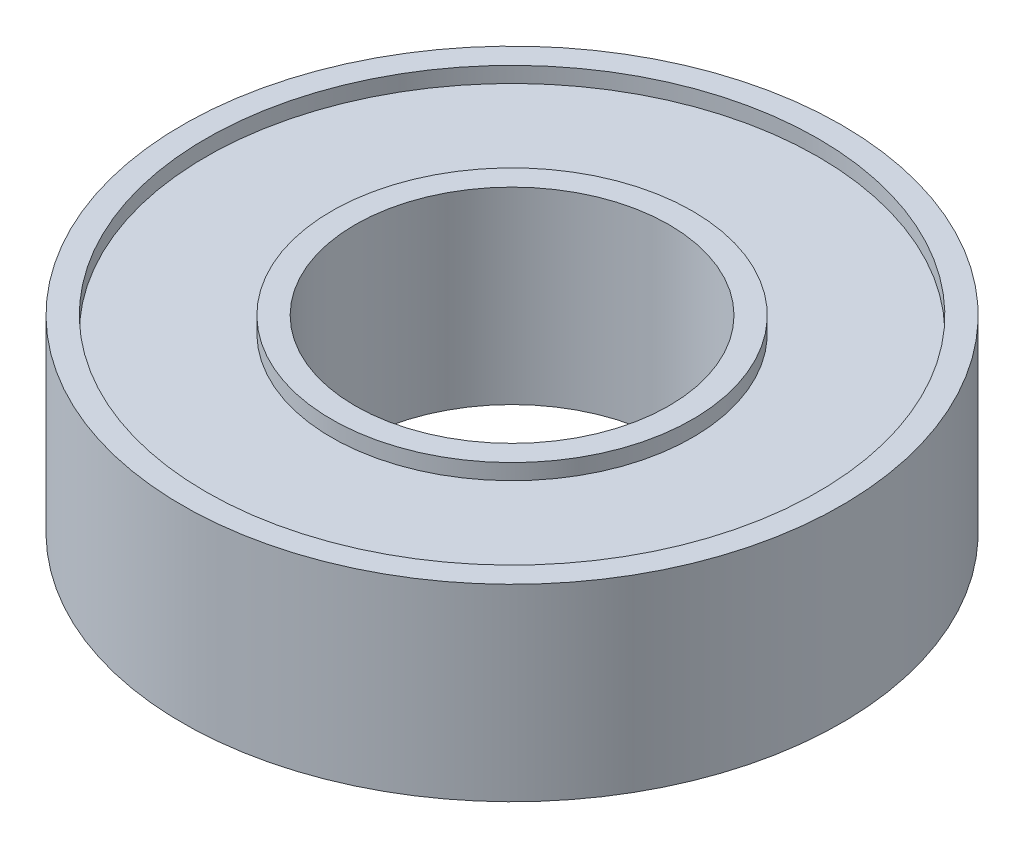
SolidWorks part; units mm, degrees
ref_plane "Alzado" through (0, 0, 0) normal (0, 0, 1) x (1, 0, 0)
ref_plane "Planta" through (0, 0, 0) normal (0, 1, 0) x (1, 0, 0)
ref_plane "Vista lateral" through (0, 0, 0) normal (1, 0, 0) x (0, 0, -1)
sketch "Croquis1" plane through (0, 0, 0) normal (0, 0, 1) x (1, 0, 0)
  line L0 (0, 0) -> (0, 16.452) construction
  line L1 (-10, 6.8567) -> (-10, 18.8567)
  line L2 (-10, 18.8567) -> (-11.5, 18.8567)
  line L3 (-11.5, 18.8567) -> (-11.5, 17.8567)
  line L4 (-11.5, 17.8567) -> (-19.5, 17.8567)
  line L5 (-19.5, 17.8567) -> (-19.5, 18.8567)
  line L6 (-19.5, 18.8567) -> (-21, 18.8567)
  line L7 (-21, 18.8567) -> (-21, 6.8567)
  line L8 (-21, 6.8567) -> (-19.5, 6.8567)
  line L9 (-19.5, 6.8567) -> (-19.5, 7.8567)
  line L10 (-19.5, 7.8567) -> (-11.5, 7.8567)
  line L11 (-11.5, 7.8567) -> (-11.5, 6.8567)
  line L12 (-11.5, 6.8567) -> (-10, 6.8567)
  dimension "D1" = 21
  dimension "D2" = 1.5
  dimension "D3" = 1
  dimension "D4" = 1
  dimension "D5" = 12
  dimension "D6" = 10
revolve "Revolución1" add sketch "Croquis1" angle 360 about L0
